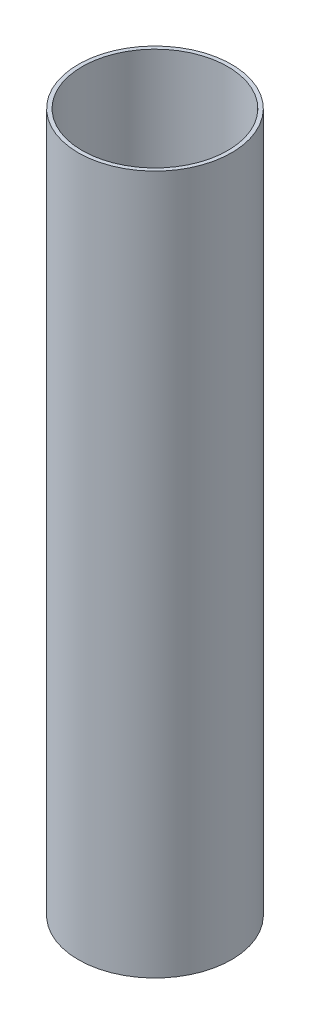
SolidWorks part; units mm, degrees
ref_plane "Front Plane" through (0, 0, 0) normal (0, 0, 1) x (1, 0, 0)
ref_plane "Top Plane" through (0, 0, 0) normal (0, 1, 0) x (1, 0, 0)
ref_plane "Right Plane" through (0, 0, 0) normal (1, 0, 0) x (0, 0, -1)
sketch "Sketch1" plane through (0, 0, 0) normal (0, 1, 0) x (1, 0, 0)
  circle A0 centre (0, 0) radius 31.25
  circle A1 centre (0, 0) radius 32.9
  dimension "D1" = 65.8
  dimension "D2" = 62.5
extrude "Boss-Extrude1" add sketch "Sketch1" along normal mid plane 300
